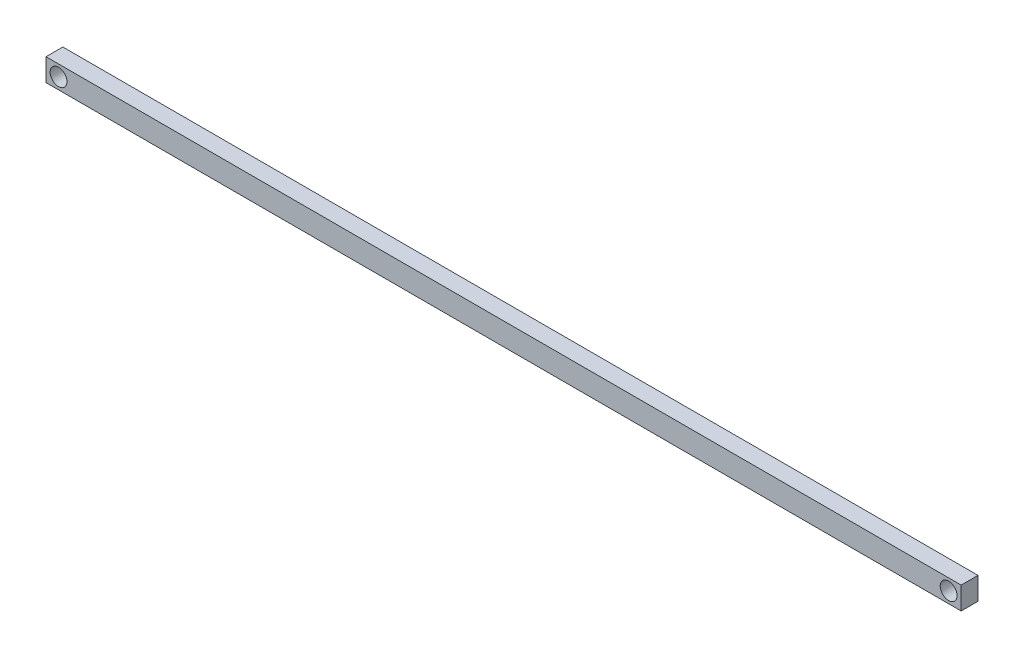
SolidWorks part; units mm, degrees
ref_plane "Front Plane" through (0, 0, 0) normal (0, 0, 1) x (1, 0, 0)
ref_plane "Top Plane" through (0, 0, 0) normal (0, 1, 0) x (1, 0, 0)
ref_plane "Right Plane" through (0, 0, 0) normal (1, 0, 0) x (0, 0, -1)
sketch "Sketch1" plane through (0, 0, 0) normal (0, 0, 1) x (1, 0, 0)
  line L1 (-407.5, 10) -> (407.5, 10)
  line L2 (-407.5, 10) -> (-407.5, -10)
  line L3 (-407.5, -10) -> (407.5, -10)
  line L4 (407.5, 10) -> (407.5, -10)
  line L5 (-407.5, 10) -> (407.5, -10) construction
  line L6 (-407.5, -10) -> (407.5, 10) construction
  circle A0 centre (-396.345, 0) radius 7.5
  circle A1 centre (396.345, 0) radius 7.5
  point P0 (0, 0)
  dimension "D4" = 15
  dimension "D5" = 15
  dimension "D1" = 815
  dimension "D2" = 792.69
  dimension "D3" = 396.345
  dimension "D6" = 20
extrude "Boss-Extrude1" add sketch "Sketch1" along normal blind 15
